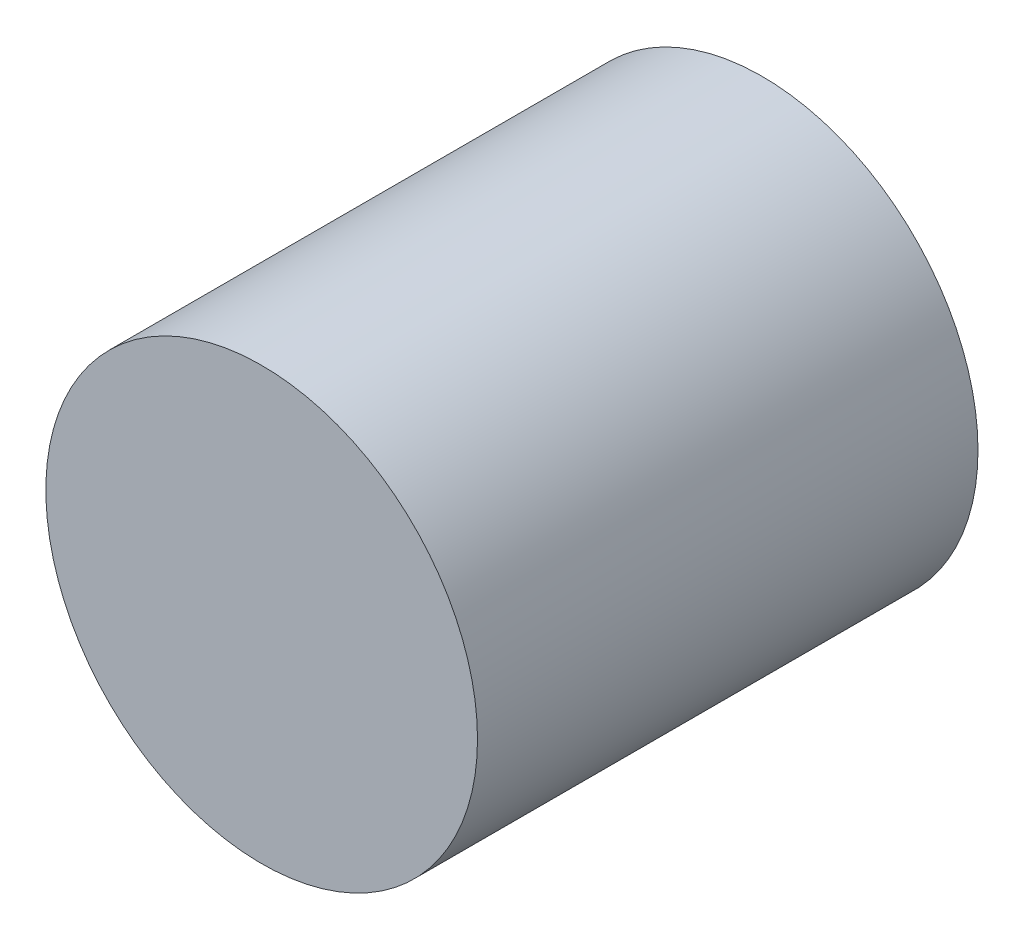
SolidWorks part; units mm, degrees
ref_plane "Front Plane" through (0, 0, 0) normal (0, 0, 1) x (1, 0, 0)
ref_plane "Top Plane" through (0, 0, 0) normal (0, 1, 0) x (1, 0, 0)
ref_plane "Right Plane" through (0, 0, 0) normal (1, 0, 0) x (0, 0, -1)
sketch "Sketch1" plane through (0, 0, 0) normal (0, 0, 1) x (1, 0, 0)
  circle A0 centre (0, 0) radius 1.7526
extrude "Boss-Extrude1" add sketch "Sketch1" along normal blind 4.064
